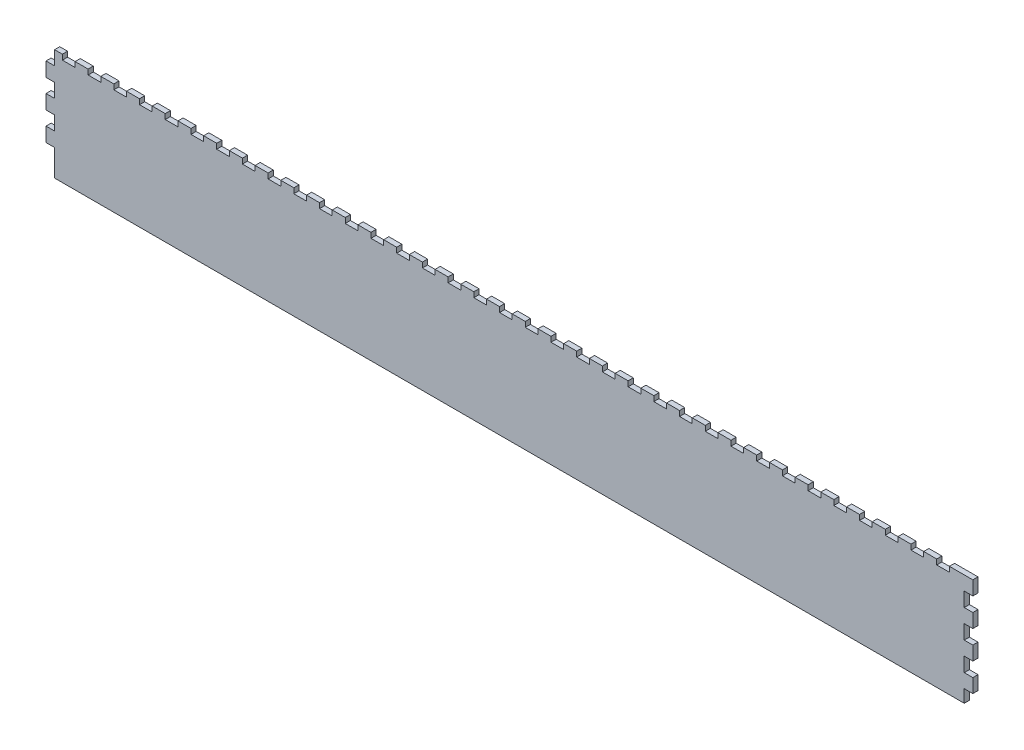
SolidWorks part; units mm, degrees
material "Perspex (TM) GS Acrylic Cast Sheet"
ref_plane "Front Plane" through (0, 0, 0) normal (0, 0, 1) x (1, 0, 0)
ref_plane "Top Plane" through (0, 0, 0) normal (0, 1, 0) x (1, 0, 0)
ref_plane "Right Plane" through (0, 0, 0) normal (1, 0, 0) x (0, 0, -1)
sketch "Sketch1" plane through (0, 0, 0) normal (0, 0, 1) x (1, 0, 0)
  line L0 (4.9997, 15.394) -> (4.9997, 0)
  line L1158 (538.3599, 64.6) -> (524.7414, 64.6)
  line L1159 (524.7414, 61.6) -> (524.7414, 64.6)
  line L1160 (524.7414, 61.6) -> (517.3729, 61.6)
  line L1161 (517.3729, 61.6) -> (517.3729, 64.6)
  line L1162 (517.3729, 64.6) -> (509.8045, 64.6)
  line L1163 (509.8045, 61.6) -> (509.8045, 64.6)
  line L1164 (509.8045, 61.6) -> (502.436, 61.6)
  line L1165 (502.436, 61.6) -> (502.436, 64.6)
  line L1166 (502.436, 64.6) -> (494.8676, 64.6)
  line L1167 (494.8676, 61.6) -> (494.8676, 64.6)
  line L1168 (494.8676, 61.6) -> (487.4991, 61.6)
  line L1169 (487.4991, 61.6) -> (487.4991, 64.6)
  line L1170 (487.4991, 64.6) -> (479.9307, 64.6)
  line L1171 (479.9307, 61.6) -> (479.9307, 64.6)
  line L1172 (479.9307, 61.6) -> (472.5622, 61.6)
  line L1173 (472.5622, 61.6) -> (472.5622, 64.6)
  line L1174 (472.5622, 64.6) -> (464.9938, 64.6)
  line L1175 (464.9938, 61.6) -> (464.9938, 64.6)
  line L1176 (464.9938, 61.6) -> (457.6253, 61.6)
  line L1177 (457.6253, 61.6) -> (457.6253, 64.6)
  line L1178 (457.6253, 64.6) -> (450.0567, 64.6)
  line L1179 (450.0567, 61.6) -> (450.0567, 64.6)
  line L1180 (450.0567, 61.6) -> (442.6886, 61.6)
  line L1181 (442.6886, 61.6) -> (442.6886, 64.6)
  line L1182 (442.6886, 64.6) -> (435.1201, 64.6)
  line L1183 (435.1201, 61.6) -> (435.1201, 64.6)
  line L1184 (435.1201, 61.6) -> (427.7516, 61.6)
  line L1185 (427.7516, 61.6) -> (427.7516, 64.6)
  line L1186 (427.7516, 64.6) -> (420.1831, 64.6)
  line L1187 (420.1831, 61.6) -> (420.1831, 64.6)
  line L1188 (420.1831, 61.6) -> (412.8147, 61.6)
  line L1189 (412.8147, 61.6) -> (412.8147, 64.6)
  line L1190 (412.8147, 64.6) -> (405.2462, 64.6)
  line L1191 (405.2462, 61.6) -> (405.2462, 64.6)
  line L1192 (405.2462, 61.6) -> (397.8777, 61.6)
  line L1193 (397.8777, 61.6) -> (397.8777, 64.6)
  line L1194 (397.8777, 64.6) -> (390.3092, 64.6)
  line L1195 (390.3092, 61.6) -> (390.3092, 64.6)
  line L1196 (390.3092, 61.6) -> (382.9407, 61.6)
  line L1197 (382.9407, 61.6) -> (382.9407, 64.6)
  line L1198 (382.9407, 64.6) -> (375.3722, 64.6)
  line L1199 (375.3722, 61.6) -> (375.3722, 64.6)
  line L1200 (375.3722, 61.6) -> (368.0038, 61.6)
  line L1201 (368.0038, 61.6) -> (368.0038, 64.6)
  line L1202 (368.0038, 64.6) -> (360.4356, 64.6)
  line L1203 (360.4356, 61.6) -> (360.4356, 64.6)
  line L1204 (360.4356, 61.6) -> (353.0672, 61.6)
  line L1205 (353.0672, 61.6) -> (353.0672, 64.6)
  line L1206 (353.0672, 64.6) -> (345.4986, 64.6)
  line L1207 (345.4986, 61.6) -> (345.4986, 64.6)
  line L1208 (345.4986, 61.6) -> (338.1302, 61.6)
  line L1209 (338.1302, 61.6) -> (338.1302, 64.6)
  line L1210 (338.1302, 64.6) -> (330.5617, 64.6)
  line L1211 (330.5617, 61.6) -> (330.5617, 64.6)
  line L1212 (330.5617, 61.6) -> (323.1932, 61.6)
  line L1213 (323.1932, 61.6) -> (323.1932, 64.6)
  line L1214 (323.1932, 64.6) -> (315.6247, 64.6)
  line L1215 (315.6247, 61.6) -> (315.6247, 64.6)
  line L1216 (315.6247, 61.6) -> (308.2563, 61.6)
  line L1217 (308.2563, 61.6) -> (308.2563, 64.6)
  line L1218 (308.2563, 64.6) -> (300.6878, 64.6)
  line L1219 (300.6878, 61.6) -> (300.6878, 64.6)
  line L1220 (300.6878, 61.6) -> (293.3193, 61.6)
  line L1221 (293.3193, 61.6) -> (293.3193, 64.6)
  line L1222 (293.3193, 64.6) -> (285.7508, 64.6)
  line L1223 (285.7508, 61.6) -> (285.7508, 64.6)
  line L1224 (285.7508, 61.6) -> (278.3823, 61.6)
  line L1225 (278.3823, 61.6) -> (278.3823, 64.6)
  line L1226 (278.3823, 64.6) -> (270.8142, 64.6)
  line L1227 (270.8142, 61.6) -> (270.8142, 64.6)
  line L1228 (270.8142, 61.6) -> (263.4457, 61.6)
  line L1229 (263.4457, 61.6) -> (263.4457, 64.6)
  line L1230 (263.4457, 64.6) -> (255.8772, 64.6)
  line L1231 (255.8772, 61.6) -> (255.8772, 64.6)
  line L1232 (255.8772, 61.6) -> (248.5088, 61.6)
  line L1233 (248.5088, 61.6) -> (248.5087, 64.6)
  line L1234 (248.5087, 64.6) -> (240.9403, 64.6)
  line L1235 (240.9403, 61.6) -> (240.9403, 64.6)
  line L1236 (240.9403, 61.6) -> (233.5718, 61.6)
  line L1237 (233.5718, 61.6) -> (233.5718, 64.6)
  line L1238 (233.5718, 64.6) -> (226.0033, 64.6)
  line L1239 (226.0033, 61.6) -> (226.0033, 64.6)
  line L1240 (226.0033, 61.6) -> (218.6348, 61.6)
  line L1241 (218.6348, 61.6) -> (218.6348, 64.6)
  line L1242 (218.6348, 64.6) -> (211.0664, 64.6)
  line L1243 (211.0664, 61.6) -> (211.0664, 64.6)
  line L1244 (211.0664, 61.6) -> (203.6979, 61.6)
  line L1245 (203.6979, 61.6) -> (203.6979, 64.6)
  line L1246 (203.6979, 64.6) -> (196.1297, 64.6)
  line L1247 (196.1297, 61.6) -> (196.1297, 64.6)
  line L1248 (196.1297, 61.6) -> (188.7613, 61.6)
  line L1249 (188.7613, 61.6) -> (188.7613, 64.6)
  line L1250 (188.7613, 64.6) -> (181.1928, 64.6)
  line L1251 (181.1928, 61.6) -> (181.1928, 64.6)
  line L1252 (181.1928, 61.6) -> (173.8243, 61.6)
  line L1253 (173.8243, 61.6) -> (173.8243, 64.6)
  line L1254 (173.8243, 64.6) -> (166.2558, 64.6)
  line L1255 (166.2558, 61.6) -> (166.2558, 64.6)
  line L1256 (166.2558, 61.6) -> (158.8873, 61.6)
  line L1257 (158.8873, 61.6) -> (158.8873, 64.6)
  line L1258 (158.8873, 64.6) -> (151.3188, 64.6)
  line L1259 (151.3188, 61.6) -> (151.3188, 64.6)
  line L1260 (151.3188, 61.6) -> (143.9504, 61.6)
  line L1261 (143.9504, 61.6) -> (143.9504, 64.6)
  line L1262 (143.9504, 64.6) -> (136.3819, 64.6)
  line L1263 (136.3819, 61.6) -> (136.3819, 64.6)
  line L1264 (136.3819, 61.6) -> (129.0134, 61.6)
  line L1265 (129.0134, 61.6) -> (129.0134, 64.6)
  line L1266 (129.0134, 64.6) -> (121.4449, 64.6)
  line L1267 (121.4449, 61.6) -> (121.4449, 64.6)
  line L1268 (121.4449, 61.6) -> (114.0764, 61.6)
  line L1269 (114.0764, 61.6) -> (114.0764, 64.6)
  line L1270 (114.0764, 64.6) -> (106.5083, 64.6)
  line L1271 (106.5083, 61.6) -> (106.5083, 64.6)
  line L1272 (106.5083, 61.6) -> (99.1398, 61.6)
  line L1273 (99.1398, 61.6) -> (99.1398, 64.6)
  line L1274 (99.1398, 64.6) -> (91.5713, 64.6)
  line L1275 (91.5713, 61.6) -> (91.5713, 64.6)
  line L1276 (91.5713, 61.6) -> (84.2029, 61.6)
  line L1277 (84.2029, 61.6) -> (84.2029, 64.6)
  line L1278 (84.2029, 64.6) -> (76.6344, 64.6)
  line L1279 (76.6344, 61.6) -> (76.6344, 64.6)
  line L1280 (76.6344, 61.6) -> (69.2659, 61.6)
  line L1281 (69.2659, 61.6) -> (69.2659, 64.6)
  line L1282 (69.2659, 64.6) -> (61.6974, 64.6)
  line L1283 (61.6974, 61.6) -> (61.6974, 64.6)
  line L1284 (61.6974, 61.6) -> (54.3289, 61.6)
  line L1285 (54.3289, 61.6) -> (54.3289, 64.6)
  line L1286 (54.3289, 64.6) -> (46.7604, 64.6)
  line L1287 (46.7604, 61.6) -> (46.7604, 64.6)
  line L1288 (46.7604, 61.6) -> (39.392, 61.6)
  line L1289 (39.392, 61.6) -> (39.392, 64.6)
  line L1290 (39.392, 64.6) -> (31.8235, 64.6)
  line L1291 (31.8235, 61.6) -> (31.8235, 64.6)
  line L1292 (31.8235, 61.6) -> (24.4554, 61.6)
  line L1293 (24.4554, 61.6) -> (24.4554, 64.6)
  line L1294 (24.4554, 64.6) -> (16.8869, 64.6)
  line L1295 (16.8869, 61.6) -> (16.8869, 64.6)
  line L1296 (16.8869, 61.6) -> (9.5184, 61.6)
  line L1297 (9.5184, 61.6) -> (9.5184, 64.6)
  line L1298 (9.5184, 64.6) -> (4.9997, 64.6)
  line L1299 (538.3599, 64.6) -> (538.3599, 56.4542)
  line L1300 (533.3598, 56.4542) -> (538.3599, 56.4542)
  line L1301 (533.3598, 56.4542) -> (533.3598, 48.1649)
  line L1302 (533.3598, 48.1649) -> (538.3599, 48.1649)
  line L1303 (538.3599, 48.1649) -> (538.3599, 40.0757)
  line L1304 (533.3598, 40.0757) -> (538.3599, 40.0757)
  line L1305 (533.3598, 40.0757) -> (533.3598, 31.7864)
  line L1306 (533.3598, 31.7864) -> (538.3599, 31.7864)
  line L1307 (538.3599, 31.7864) -> (538.3599, 23.7267)
  line L1308 (4.9997, 64.6) -> (4.9997, 56.4542)
  line L1309 (0, 56.4542) -> (4.9997, 56.4542)
  line L1310 (0, 56.4542) -> (0, 48.1649)
  line L1311 (0, 48.1649) -> (4.9997, 48.1649)
  line L1312 (4.9997, 48.1649) -> (4.9997, 40.0757)
  line L1313 (0, 40.0757) -> (4.9997, 40.0757)
  line L1314 (0, 40.0757) -> (0, 31.7864)
  line L1315 (0, 31.7864) -> (4.9997, 31.7864)
  line L1316 (4.9997, 31.7864) -> (4.9997, 23.6833)
  line L1317 (4.9997, 0) -> (533.3598, 0)
  line L1318 (533.3598, 23.7267) -> (538.3599, 23.7267)
  line L1319 (533.3598, 23.7267) -> (533.3598, 15.4209)
  line L1320 (533.3598, 15.4209) -> (538.3599, 15.4209)
  line L1321 (538.3599, 15.4209) -> (538.3599, 7.3612)
  line L1322 (533.3598, 7.3612) -> (538.3599, 7.3612)
  line L1323 (533.3598, 7.3612) -> (533.3598, 0)
  line L1324 (0, 23.6833) -> (4.9997, 23.6833)
  line L1325 (0, 23.6833) -> (0, 15.394)
  line L1326 (0, 15.394) -> (4.9997, 15.394)
extrude "Boss-Extrude1" add sketch "Sketch1" along normal blind 3
sketch "Sketch3" plane through (0, 0, 3) normal (0, 0, 1) x (1, 0, 0)
  line L0 (427.3689, 43.3788) -> (427.3689, 36.9916)
  line L1 (427.3689, 36.9916) -> (432.9032, 36.9916)
  line L2 (432.9032, 36.9916) -> (438.4376, 36.9916)
  line L3 (438.4376, 36.9916) -> (438.4376, 35.1468)
  line L4 (438.4376, 35.1468) -> (438.4376, 33.3021)
  line L5 (438.4376, 33.3021) -> (432.9032, 33.3021)
  line L6 (432.9032, 33.3021) -> (427.3689, 33.3021)
  line L7 (427.3689, 33.3021) -> (427.3689, 21.0804)
  line L8 (427.3689, 21.0804) -> (427.3689, 8.8587)
  line L9 (427.3689, 8.8587) -> (431.0585, 8.8587)
  line L10 (431.0585, 8.8587) -> (434.748, 8.8587)
  line L11 (434.748, 8.8587) -> (434.748, 17.3908)
  line L12 (434.748, 17.3908) -> (434.748, 25.923)
  line L13 (434.748, 25.923) -> (436.5928, 25.923)
  line L14 (436.5928, 25.923) -> (438.4376, 25.923)
  line L15 (438.4376, 25.923) -> (438.4376, 17.3908)
  line L16 (438.4376, 17.3908) -> (438.4376, 8.8587)
  line L17 (438.4376, 8.8587) -> (442.1271, 8.8587)
  line L18 (442.1271, 8.8587) -> (445.8167, 8.8587)
  line L19 (445.8167, 8.8587) -> (445.8133, 26.4994)
  line L20 (444.0744, 29.4972) -> (443.885, 10.7035)
  line L21 (443.885, 10.7035) -> (442.0836, 10.7035)
  line L22 (442.0836, 10.7035) -> (440.2822, 10.7035)
  line L23 (440.2822, 10.7035) -> (440.2822, 19.2356)
  line L24 (440.2822, 19.2356) -> (440.2822, 27.7677)
  line L25 (440.2822, 27.7677) -> (436.5926, 27.7677)
  line L26 (436.5926, 27.7677) -> (432.9031, 27.7677)
  line L27 (432.9031, 27.7677) -> (432.9031, 19.2356)
  line L28 (432.9031, 19.2356) -> (432.9031, 10.7035)
  line L29 (432.9031, 10.7035) -> (431.0583, 10.7035)
  line L30 (431.0583, 10.7035) -> (429.2135, 10.7035)
  line L31 (429.2135, 10.7035) -> (429.2135, 21.0804)
  line L32 (429.2135, 21.0804) -> (429.2135, 31.4573)
  line L33 (429.2135, 31.4573) -> (434.7478, 31.4573)
  line L34 (434.7478, 31.4573) -> (440.2822, 31.4573)
  line L35 (440.2822, 31.4573) -> (440.2822, 35.1468)
  line L36 (440.2822, 35.1468) -> (440.2822, 38.8364)
  line L37 (440.2822, 38.8364) -> (434.8154, 38.8364)
  line L38 (434.8154, 38.8364) -> (429.3486, 38.8364)
  line L39 (429.3486, 38.8364) -> (429.0745, 46.5614)
  line L40 (427.679, 53.4098) -> (427.6792, 53.4098)
  line L41 (317.1431, 29.0623) -> (317.1431, 8.8199)
  line L42 (317.1431, 8.8199) -> (320.7174, 8.9546)
  line L43 (320.7174, 8.9546) -> (324.2916, 9.0893)
  line L44 (324.2916, 9.0893) -> (326.2203, 14.6236)
  line L45 (326.2203, 14.6236) -> (328.149, 20.158)
  line L46 (328.149, 20.158) -> (328.1804, 14.5083)
  line L47 (328.1804, 14.5083) -> (328.2118, 8.8587)
  line L48 (328.2118, 8.8587) -> (331.9014, 8.8587)
  line L49 (331.9014, 8.8587) -> (335.5909, 8.8587)
  line L50 (335.5909, 8.8587) -> (335.5878, 27.6524)
  line L51 (333.8679, 30.4196) -> (333.6625, 10.7035)
  line L52 (333.6625, 10.7035) -> (331.8686, 10.7035)
  line L53 (331.8686, 10.7035) -> (330.0747, 10.7035)
  line L54 (330.0747, 10.7035) -> (329.9504, 20.7161)
  line L55 (329.9504, 20.7161) -> (329.8261, 30.7288)
  line L56 (329.8261, 30.7288) -> (326.41, 20.7161)
  line L57 (326.41, 20.7161) -> (322.9939, 10.7035)
  line L58 (322.9939, 10.7035) -> (321.0268, 10.7035)
  line L59 (321.0268, 10.7035) -> (319.0597, 10.7035)
  line L60 (319.0597, 10.7035) -> (318.8681, 32.2644)
  line L61 (317.4535, 52.9486) -> (317.4534, 52.9486)
  line L62 (299.1565, 42.9176) -> (299.1565, 36.9916)
  line L63 (299.1565, 36.9916) -> (302.846, 36.9916)
  line L64 (302.846, 36.9916) -> (306.5356, 36.9916)
  line L65 (306.5356, 36.9916) -> (306.5325, 40.1047)
  line L66 (304.9009, 43.9062) -> (304.5723, 38.8364)
  line L67 (304.5723, 38.8364) -> (302.8566, 38.8364)
  line L68 (302.8566, 38.8364) -> (301.1409, 38.8364)
  line L69 (301.1409, 38.8364) -> (300.8784, 46.9617)
  line L70 (299.4568, 52.3947) -> (299.4566, 52.3947)
  line L71 (340.6641, 28.8511) -> (340.6641, 8.8587)
  line L72 (340.6641, 8.8587) -> (349.888, 8.8587)
  line L73 (349.888, 8.8587) -> (359.1119, 8.8587)
  line L74 (359.1119, 8.8587) -> (359.1088, 26.73)
  line L75 (357.3698, 29.7278) -> (357.1812, 10.7035)
  line L76 (357.1812, 10.7035) -> (349.8842, 10.7035)
  line L77 (349.8842, 10.7035) -> (342.5872, 10.7035)
  line L78 (342.5872, 10.7035) -> (342.4078, 32.2644)
  line L79 (340.9694, 52.4545) -> (340.9693, 52.4545)
  line L80 (380.7881, 28.8511) -> (380.7881, 8.8587)
  line L81 (380.7881, 8.8587) -> (390.012, 8.8587)
  line L82 (390.012, 8.8587) -> (399.2359, 8.8587)
  line L83 (399.2359, 8.8587) -> (399.2328, 26.73)
  line L84 (397.4938, 29.7278) -> (397.3053, 10.7035)
  line L85 (397.3053, 10.7035) -> (390.0083, 10.7035)
  line L86 (390.0083, 10.7035) -> (382.7113, 10.7035)
  line L87 (382.7113, 10.7035) -> (382.5318, 32.2644)
  line L88 (381.0935, 52.4545) -> (381.0934, 52.4545)
  line L89 (132.8326, 45.6391) -> (132.5214, 38.8364)
  line L90 (132.5214, 38.8364) -> (127.0587, 38.8364)
  line L91 (127.0587, 38.8364) -> (121.5961, 38.8364)
  line L92 (121.5961, 38.8364) -> (121.5961, 35.1468)
  line L93 (121.5961, 35.1468) -> (121.5961, 31.4573)
  line L94 (121.5961, 31.4573) -> (127.1304, 31.4573)
  line L95 (127.1304, 31.4573) -> (132.6648, 31.4573)
  line L96 (132.6648, 31.4573) -> (132.6648, 29.6125)
  line L97 (132.6648, 29.6125) -> (132.6648, 27.7677)
  line L98 (132.6648, 27.7677) -> (127.1304, 27.7677)
  line L99 (127.1304, 27.7677) -> (121.5961, 27.7677)
  line L100 (121.5961, 27.7677) -> (121.5961, 21.0804)
  line L101 (121.5961, 21.0804) -> (121.5961, 14.393)
  line L102 (121.5961, 14.393) -> (125.2857, 14.393)
  line L103 (125.2857, 14.393) -> (128.9752, 14.393)
  line L104 (128.9752, 14.393) -> (128.9752, 17.1602)
  line L105 (128.9752, 17.1602) -> (128.9752, 19.9274)
  line L106 (128.9752, 19.9274) -> (130.82, 19.9274)
  line L107 (130.82, 19.9274) -> (132.6648, 19.9274)
  line L108 (132.6648, 19.9274) -> (132.6648, 15.3154)
  line L109 (132.6648, 15.3154) -> (132.6648, 10.7035)
  line L110 (132.6648, 10.7035) -> (125.3275, 10.7035)
  line L111 (125.3275, 10.7035) -> (117.9903, 10.7035)
  line L112 (117.9903, 10.7035) -> (117.8044, 30.4196)
  line L113 (116.0617, 27.0063) -> (116.0617, 8.8587)
  line L115 (116.0617, 8.8587) -> (125.2857, 8.8587)
  line L116 (125.2857, 8.8587) -> (134.5095, 8.8587)
  line L117 (134.5095, 8.8587) -> (134.5095, 15.3154)
  line L118 (134.5095, 15.3154) -> (134.5095, 21.7722)
  line L119 (134.5095, 21.7722) -> (130.82, 21.7722)
  line L120 (130.82, 21.7722) -> (127.1304, 21.7722)
  line L121 (127.1304, 21.7722) -> (127.1304, 19.005)
  line L122 (127.1304, 19.005) -> (127.1304, 16.2378)
  line L123 (127.1304, 16.2378) -> (125.2857, 16.2378)
  line L124 (125.2857, 16.2378) -> (123.4408, 16.2378)
  line L125 (123.4408, 16.2378) -> (123.4408, 21.0804)
  line L126 (123.4408, 21.0804) -> (123.4408, 25.9229)
  line L127 (123.4408, 25.9229) -> (128.9752, 25.9229)
  line L128 (128.9752, 25.9229) -> (134.5095, 25.9229)
  line L129 (134.5095, 25.9229) -> (134.5095, 29.6125)
  line L130 (134.5095, 29.6125) -> (134.5095, 33.3021)
  line L131 (134.5095, 33.3021) -> (128.9752, 33.3021)
  line L132 (128.9752, 33.3021) -> (123.4408, 33.3021)
  line L133 (123.4408, 33.3021) -> (123.4408, 35.1468)
  line L134 (123.4408, 35.1468) -> (123.4408, 36.9916)
  line L135 (123.4408, 36.9916) -> (128.9752, 36.9916)
  line L136 (128.9752, 36.9916) -> (134.5095, 36.9916)
  line L137 (134.5095, 36.9916) -> (134.4639, 43.5637)
  line L138 (179.4133, 45.6391) -> (179.1021, 38.8364)
  line L139 (179.1021, 38.8364) -> (173.6395, 38.8364)
  line L140 (173.6395, 38.8364) -> (168.1768, 38.8364)
  line L141 (168.1768, 38.8364) -> (168.1768, 35.1468)
  line L142 (168.1768, 35.1468) -> (168.1768, 31.4573)
  line L143 (168.1768, 31.4573) -> (173.7112, 31.4573)
  line L144 (173.7112, 31.4573) -> (179.2455, 31.4573)
  line L145 (179.2455, 31.4573) -> (179.2455, 29.6125)
  line L146 (179.2455, 29.6125) -> (179.2455, 27.7677)
  line L147 (179.2455, 27.7677) -> (173.7112, 27.7677)
  line L148 (173.7112, 27.7677) -> (168.1768, 27.7677)
  line L149 (168.1768, 27.7677) -> (168.1768, 21.0804)
  line L150 (168.1768, 21.0804) -> (168.1768, 14.393)
  line L151 (168.1768, 14.393) -> (171.8664, 14.393)
  line L152 (171.8664, 14.393) -> (175.556, 14.393)
  line L153 (175.556, 14.393) -> (175.556, 17.1602)
  line L154 (175.556, 17.1602) -> (175.556, 19.9274)
  line L155 (175.556, 19.9274) -> (177.4008, 19.9274)
  line L156 (177.4008, 19.9274) -> (179.2455, 19.9274)
  line L157 (179.2455, 19.9274) -> (179.2455, 15.3154)
  line L158 (179.2455, 15.3154) -> (179.2455, 10.7035)
  line L159 (179.2455, 10.7035) -> (171.9083, 10.7035)
  line L160 (171.9083, 10.7035) -> (164.571, 10.7035)
  line L161 (164.571, 10.7035) -> (164.3852, 30.4196)
  line L162 (162.6425, 27.0063) -> (162.6425, 8.8587)
  line L163 (162.6425, 8.8587) -> (171.8664, 8.8587)
  line L164 (171.8664, 8.8587) -> (181.0903, 8.8587)
  line L165 (181.0903, 8.8587) -> (181.0903, 15.3154)
  line L166 (181.0903, 15.3154) -> (181.0903, 21.7722)
  line L167 (181.0903, 21.7722) -> (177.4008, 21.7722)
  line L168 (177.4008, 21.7722) -> (173.7112, 21.7722)
  line L169 (173.7112, 21.7722) -> (173.7112, 19.005)
  line L170 (173.7112, 19.005) -> (173.7112, 16.2378)
  line L171 (173.7112, 16.2378) -> (171.8664, 16.2378)
  line L172 (171.8664, 16.2378) -> (170.0216, 16.2378)
  line L173 (170.0216, 16.2378) -> (170.0216, 21.0804)
  line L174 (170.0216, 21.0804) -> (170.0216, 25.9229)
  line L175 (170.0216, 25.9229) -> (175.556, 25.9229)
  line L176 (175.556, 25.9229) -> (181.0903, 25.9229)
  line L177 (181.0903, 25.9229) -> (181.0903, 29.6125)
  line L178 (181.0903, 29.6125) -> (181.0903, 33.3021)
  line L179 (181.0903, 33.3021) -> (175.556, 33.3021)
  line L180 (175.556, 33.3021) -> (170.0216, 33.3021)
  line L181 (170.0216, 33.3021) -> (170.0216, 35.1468)
  line L182 (170.0216, 35.1468) -> (170.0216, 36.9916)
  line L183 (170.0216, 36.9916) -> (175.556, 36.9916)
  line L184 (175.556, 36.9916) -> (181.0903, 36.9916)
  line L185 (181.0903, 36.9916) -> (181.0447, 43.5637)
  line L186 (264.2733, 45.6391) -> (263.9622, 38.8364)
  line L187 (263.9622, 38.8364) -> (258.4995, 38.8364)
  line L188 (258.4995, 38.8364) -> (253.0369, 38.8364)
  line L189 (253.0369, 38.8364) -> (253.0369, 35.1468)
  line L190 (253.0369, 35.1468) -> (253.0369, 31.4573)
  line L191 (253.0369, 31.4573) -> (258.5712, 31.4573)
  line L192 (258.5712, 31.4573) -> (264.1056, 31.4573)
  line L193 (264.1056, 31.4573) -> (264.1056, 29.6125)
  line L194 (264.1056, 29.6125) -> (264.1056, 27.7677)
  line L195 (264.1056, 27.7677) -> (258.5712, 27.7677)
  line L196 (258.5712, 27.7677) -> (253.0369, 27.7677)
  line L197 (253.0369, 27.7677) -> (253.0369, 21.0804)
  line L198 (253.0369, 21.0804) -> (253.0369, 14.393)
  line L199 (253.0369, 14.393) -> (256.7264, 14.393)
  line L200 (256.7264, 14.393) -> (260.416, 14.393)
  line L201 (260.416, 14.393) -> (260.416, 17.1602)
  line L202 (260.416, 17.1602) -> (260.416, 19.9274)
  line L203 (260.416, 19.9274) -> (262.2608, 19.9274)
  line L204 (262.2608, 19.9274) -> (264.1056, 19.9274)
  line L205 (264.1056, 19.9274) -> (264.1056, 15.3154)
  line L206 (264.1056, 15.3154) -> (264.1056, 10.7035)
  line L207 (264.1056, 10.7035) -> (256.7683, 10.7035)
  line L208 (256.7683, 10.7035) -> (249.4311, 10.7035)
  line L209 (249.4311, 10.7035) -> (249.2452, 30.4196)
  line L210 (247.5025, 27.0063) -> (247.5025, 8.8587)
  line L211 (247.5025, 8.8587) -> (256.7264, 8.8587)
  line L212 (256.7264, 8.8587) -> (265.9504, 8.8587)
  line L213 (265.9504, 8.8587) -> (265.9504, 15.3154)
  line L214 (265.9504, 15.3154) -> (265.9504, 21.7722)
  line L215 (265.9504, 21.7722) -> (262.2608, 21.7722)
  line L216 (262.2608, 21.7722) -> (258.5712, 21.7722)
  line L217 (258.5712, 21.7722) -> (258.5712, 19.005)
  line L218 (258.5712, 19.005) -> (258.5712, 16.2378)
  line L219 (258.5712, 16.2378) -> (256.7264, 16.2378)
  line L220 (256.7264, 16.2378) -> (254.8817, 16.2378)
  line L221 (254.8817, 16.2378) -> (254.8817, 21.0804)
  line L222 (254.8817, 21.0804) -> (254.8817, 25.9229)
  line L223 (254.8817, 25.9229) -> (260.416, 25.9229)
  line L224 (260.416, 25.9229) -> (265.9504, 25.9229)
  line L225 (265.9504, 25.9229) -> (265.9504, 29.6125)
  line L226 (265.9504, 29.6125) -> (265.9504, 33.3021)
  line L227 (265.9504, 33.3021) -> (260.416, 33.3021)
  line L228 (260.416, 33.3021) -> (254.8817, 33.3021)
  line L229 (254.8817, 33.3021) -> (254.8817, 35.1468)
  line L230 (254.8817, 35.1468) -> (254.8817, 36.9916)
  line L231 (254.8817, 36.9916) -> (260.416, 36.9916)
  line L232 (260.416, 36.9916) -> (265.9504, 36.9916)
  line L233 (265.9504, 36.9916) -> (265.9048, 43.5637)
  line L234 (139.1215, 28.1593) -> (139.1215, 8.8587)
  line L235 (139.1215, 8.8587) -> (148.3454, 8.8587)
  line L236 (148.3454, 8.8587) -> (157.5694, 8.8587)
  line L237 (157.5694, 8.8587) -> (157.5694, 18.0826)
  line L238 (155.0474, 28.419) -> (153.2173, 29.5267)
  line L239 (153.2173, 29.5267) -> (155.3933, 30.5839)
  line L240 (155.3933, 30.5839) -> (157.5694, 31.6411)
  line L241 (157.5694, 31.6411) -> (157.5237, 38.813)
  line L242 (155.7798, 40.2285) -> (155.494, 32.6103)
  line L243 (155.494, 32.6103) -> (152.871, 31.2171)
  line L244 (152.6724, 27.6912) -> (155.7246, 26.1862)
  line L245 (155.7246, 26.1862) -> (155.7246, 18.4448)
  line L246 (155.7246, 18.4448) -> (155.7246, 10.7035)
  line L247 (155.7246, 10.7035) -> (148.3856, 10.7035)
  line L248 (148.3856, 10.7035) -> (141.0465, 10.7035)
  line L249 (141.0465, 10.7035) -> (140.8647, 31.5726)
  line L250 (185.7023, 28.1593) -> (185.7023, 8.8587)
  line L251 (185.7023, 8.8587) -> (189.3919, 8.8587)
  line L252 (189.3919, 8.8587) -> (193.0814, 8.8587)
  line L253 (193.0814, 8.8587) -> (193.0814, 22.9252)
  line L254 (193.0814, 22.9252) -> (193.0814, 36.9916)
  line L255 (193.0814, 36.9916) -> (195.8486, 36.9916)
  line L256 (195.8486, 36.9916) -> (198.6158, 36.9916)
  line L257 (198.6158, 36.9916) -> (198.6127, 40.3353)
  line L258 (196.9651, 44.0249) -> (196.6398, 38.8364)
  line L259 (196.6398, 38.8364) -> (193.9383, 38.8364)
  line L260 (193.9383, 38.8364) -> (191.2368, 38.8364)
  line L261 (191.2368, 38.8364) -> (191.2368, 24.7699)
  line L262 (191.2368, 24.7699) -> (191.2368, 10.7035)
  line L263 (191.2368, 10.7035) -> (189.4321, 10.7035)
  line L264 (189.4321, 10.7035) -> (187.6274, 10.7035)
  line L265 (187.6274, 10.7035) -> (187.4457, 31.5726)
  line L266 (186.0076, 51.0709) -> (186.0075, 51.0709)
  line L267 (287.3183, 42.6413) -> (287.0333, 33.3021)
  line L268 (287.0333, 33.3021) -> (285.2545, 33.3021)
  line L269 (285.2545, 33.3021) -> (283.4758, 33.3021)
  line L270 (283.4758, 33.3021) -> (283.4758, 36.0692)
  line L271 (283.4758, 36.0692) -> (283.4758, 38.8364)
  line L272 (283.4758, 38.8364) -> (279.7862, 38.8364)
  line L273 (279.7862, 38.8364) -> (276.0967, 38.8364)
  line L274 (276.0967, 38.8364) -> (276.0967, 26.6147)
  line L275 (276.0967, 26.6147) -> (276.0967, 14.393)
  line L276 (276.0967, 14.393) -> (279.7862, 14.393)
  line L277 (279.7862, 14.393) -> (283.4758, 14.393)
  line L278 (283.4758, 14.393) -> (283.4758, 17.1602)
  line L279 (283.4758, 17.1602) -> (283.4758, 19.9274)
  line L280 (283.4758, 19.9274) -> (285.3206, 19.9274)
  line L281 (285.3206, 19.9274) -> (287.1654, 19.9274)
  line L282 (287.1654, 19.9274) -> (287.1654, 15.3154)
  line L283 (287.1654, 15.3154) -> (287.1654, 10.7035)
  line L284 (287.1654, 10.7035) -> (279.8292, 10.7035)
  line L285 (279.8292, 10.7035) -> (272.4931, 10.7035)
  line L286 (272.4931, 10.7035) -> (272.3046, 29.7278)
  line L287 (270.5623, 26.3146) -> (270.5623, 8.8587)
  line L288 (270.5623, 8.8587) -> (279.7862, 8.8587)
  line L289 (279.7862, 8.8587) -> (289.0102, 8.8587)
  line L290 (289.0102, 8.8587) -> (289.0102, 15.3154)
  line L291 (289.0102, 15.3154) -> (289.0102, 21.7722)
  line L292 (289.0102, 21.7722) -> (285.3206, 21.7722)
  line L293 (285.3206, 21.7722) -> (281.631, 21.7722)
  line L294 (281.631, 21.7722) -> (281.631, 19.005)
  line L295 (281.631, 19.005) -> (281.631, 16.2378)
  line L296 (281.631, 16.2378) -> (279.7862, 16.2378)
  line L297 (279.7862, 16.2378) -> (277.9415, 16.2378)
  line L298 (277.9415, 16.2378) -> (277.9415, 26.6147)
  line L299 (277.9415, 26.6147) -> (277.9415, 36.9916)
  line L300 (277.9415, 36.9916) -> (279.7862, 36.9916)
  line L301 (279.7862, 36.9916) -> (281.631, 36.9916)
  line L302 (281.631, 36.9916) -> (281.631, 34.2245)
  line L303 (281.631, 34.2245) -> (281.631, 31.4573)
  line L304 (281.631, 31.4573) -> (285.3206, 31.4573)
  line L305 (285.3206, 31.4573) -> (289.0102, 31.4573)
  line L306 (289.0102, 31.4573) -> (288.9645, 40.5659)
  line L307 (364.1851, 28.1593) -> (364.1851, 8.8587)
  line L308 (364.1851, 8.8587) -> (367.8746, 8.8587)
  line L309 (367.8746, 8.8587) -> (371.5642, 8.8587)
  line L310 (371.5642, 8.8587) -> (371.5642, 22.9252)
  line L311 (371.5642, 22.9252) -> (371.5642, 36.9916)
  line L312 (371.5642, 36.9916) -> (374.3314, 36.9916)
  line L313 (374.3314, 36.9916) -> (377.0985, 36.9916)
  line L314 (377.0985, 36.9916) -> (377.0954, 40.3353)
  line L315 (375.4479, 44.0249) -> (375.1226, 38.8364)
  line L316 (375.1226, 38.8364) -> (372.4211, 38.8364)
  line L317 (372.4211, 38.8364) -> (369.7196, 38.8364)
  line L318 (369.7196, 38.8364) -> (369.7196, 24.7699)
  line L319 (369.7196, 24.7699) -> (369.7196, 10.7035)
  line L320 (369.7196, 10.7035) -> (367.9149, 10.7035)
  line L321 (367.9149, 10.7035) -> (366.1102, 10.7035)
  line L322 (366.1102, 10.7035) -> (365.9284, 31.5726)
  line L323 (364.4904, 51.0709) -> (364.4903, 51.0709)
  line L324 (421.0584, 39.6435) -> (420.7948, 27.7677)
  line L325 (420.7948, 27.7677) -> (419.0087, 27.7677)
  line L326 (419.0087, 27.7677) -> (417.2226, 27.7677)
  line L327 (417.2226, 27.7677) -> (417.2226, 33.3021)
  line L328 (417.2226, 33.3021) -> (417.2226, 38.8364)
  line L329 (417.2226, 38.8364) -> (413.533, 38.8364)
  line L330 (413.533, 38.8364) -> (409.8435, 38.8364)
  line L331 (409.8435, 38.8364) -> (409.8435, 26.6147)
  line L332 (409.8435, 26.6147) -> (409.8435, 14.393)
  line L333 (409.8435, 14.393) -> (413.533, 14.393)
  line L334 (413.533, 14.393) -> (417.2226, 14.393)
  line L335 (417.2226, 14.393) -> (417.2226, 17.1602)
  line L336 (417.2226, 17.1602) -> (417.2226, 19.9274)
  line L337 (417.2226, 19.9274) -> (419.0674, 19.9274)
  line L338 (419.0674, 19.9274) -> (420.9122, 19.9274)
  line L339 (420.9122, 19.9274) -> (420.9122, 15.3154)
  line L340 (420.9122, 15.3154) -> (420.9122, 10.7035)
  line L341 (420.9122, 10.7035) -> (413.5729, 10.7035)
  line L342 (413.5729, 10.7035) -> (406.2336, 10.7035)
  line L343 (406.2336, 10.7035) -> (406.0524, 29.4972)
  line L344 (404.3091, 26.084) -> (404.3091, 8.8587)
  line L345 (404.3091, 8.8587) -> (413.533, 8.8587)
  line L346 (413.533, 8.8587) -> (422.7569, 8.8587)
  line L347 (422.7569, 8.8587) -> (422.7569, 15.3154)
  line L348 (422.7569, 15.3154) -> (422.7569, 21.7722)
  line L349 (422.7569, 21.7722) -> (419.0674, 21.7722)
  line L350 (419.0674, 21.7722) -> (415.3778, 21.7722)
  line L351 (415.3778, 21.7722) -> (415.3778, 19.005)
  line L352 (415.3778, 19.005) -> (415.3778, 16.2378)
  line L353 (415.3778, 16.2378) -> (413.533, 16.2378)
  line L354 (413.533, 16.2378) -> (411.6882, 16.2378)
  line L355 (411.6882, 16.2378) -> (411.6882, 26.6147)
  line L356 (411.6882, 26.6147) -> (411.6882, 36.9916)
  line L357 (411.6882, 36.9916) -> (413.533, 36.9916)
  line L358 (413.533, 36.9916) -> (415.3778, 36.9916)
  line L359 (415.3778, 36.9916) -> (415.3778, 31.4573)
  line L360 (415.3778, 31.4573) -> (415.3778, 25.9229)
  line L361 (415.3778, 25.9229) -> (419.0674, 25.9229)
  line L362 (419.0674, 25.9229) -> (422.7569, 25.9229)
  line L363 (422.7569, 25.9229) -> (422.7113, 37.5681)
  line L364 (310.3498, 30.4196) -> (310.1348, 10.7035)
  line L365 (310.1348, 10.7035) -> (308.3352, 10.7035)
  line L366 (308.3352, 10.7035) -> (306.5356, 10.7035)
  line L367 (306.5356, 10.7035) -> (306.5356, 22.0028)
  line L368 (306.5356, 22.0028) -> (306.5356, 33.3021)
  line L369 (306.5356, 33.3021) -> (302.846, 33.3021)
  line L370 (302.846, 33.3021) -> (299.1565, 33.3021)
  line L371 (299.1565, 33.3021) -> (299.1565, 22.0028)
  line L372 (299.1565, 22.0028) -> (299.1565, 10.7035)
  line L373 (299.1565, 10.7035) -> (297.3511, 10.7035)
  line L374 (297.3511, 10.7035) -> (295.5459, 10.7035)
  line L375 (295.5459, 10.7035) -> (295.346, 29.7278)
  line L376 (293.6249, 26.2688) -> (293.6221, 8.8587)
  line L377 (293.6221, 8.8587) -> (297.3116, 8.8587)
  line L378 (297.3116, 8.8587) -> (301.0012, 8.8587)
  line L379 (301.0012, 8.8587) -> (301.0012, 20.158)
  line L380 (301.0012, 20.158) -> (301.0012, 31.4573)
  line L381 (301.0012, 31.4573) -> (302.846, 31.4573)
  line L382 (302.846, 31.4573) -> (304.6908, 31.4573)
  line L383 (304.6908, 31.4573) -> (304.6908, 20.158)
  line L384 (304.6908, 20.158) -> (304.6908, 8.8587)
  line L385 (304.6908, 8.8587) -> (308.3803, 8.8587)
  line L386 (308.3803, 8.8587) -> (312.0699, 8.8587)
  line L387 (312.0699, 8.8587) -> (312.0243, 28.1136)
  line L388 (326.6972, 38.8364) -> (324.7528, 33.0715)
  line L389 (324.7528, 33.0715) -> (324.4665, 39.9894)
  line L390 (328.9784, 48.2909) -> (328.9785, 48.2909)
  line L391 (92.5407, 26.5451) -> (92.5407, 8.8587)
  line L392 (92.5407, 8.8587) -> (101.7647, 8.8587)
  line L393 (101.7647, 8.8587) -> (110.9886, 8.8587)
  line L394 (110.9886, 8.8587) -> (110.9886, 20.8409)
  line L395 (110.9886, 20.8409) -> (110.9886, 32.8232)
  line L396 (110.9886, 32.8232) -> (108.7994, 33.9357)
  line L397 (108.7994, 33.9357) -> (106.6103, 35.0483)
  line L398 (106.6103, 35.0483) -> (108.7994, 36.1119)
  line L399 (108.7994, 36.1119) -> (110.9886, 37.1754)
  line L400 (110.9886, 37.1754) -> (110.9429, 41.8108)
  line L401 (109.2518, 43.2178) -> (108.9132, 38.1446)
  line L402 (108.9132, 38.1446) -> (106.2902, 36.7515)
  line L403 (106.0917, 33.2256) -> (109.1438, 31.7205)
  line L404 (109.1438, 31.7205) -> (109.1438, 21.212)
  line L405 (109.1438, 21.212) -> (109.1438, 10.7035)
  line L406 (109.1438, 10.7035) -> (101.8073, 10.7035)
  line L407 (101.8073, 10.7035) -> (94.4708, 10.7035)
  line L408 (94.4708, 10.7035) -> (94.2831, 29.9584)
  line L409 (98.0751, 40.3496) -> (98.0751, 36.9289)
  line L410 (98.0751, 36.9289) -> (101.7642, 38.9203)
  line L411 (103.8574, 46.0593) -> (103.5335, 41.7382)
  line L412 (103.5335, 41.7382) -> (101.9416, 40.9791)
  line L413 (230.4383, 30.0041) -> (230.4383, 16.2378)
  line L414 (230.4383, 16.2378) -> (227.6711, 16.2378)
  line L415 (227.6711, 16.2378) -> (224.9039, 16.2378)
  line L416 (224.9039, 16.2378) -> (224.9039, 12.5483)
  line L417 (224.9039, 12.5483) -> (224.9039, 8.8587)
  line L418 (224.9039, 8.8587) -> (234.1279, 8.8587)
  line L419 (234.1279, 8.8587) -> (243.3518, 8.8587)
  line L420 (243.3518, 8.8587) -> (243.3518, 12.5483)
  line L421 (243.3518, 12.5483) -> (243.3518, 16.2378)
  line L422 (243.3518, 16.2378) -> (240.5846, 16.2378)
  line L423 (240.5846, 16.2378) -> (237.8174, 16.2378)
  line L424 (237.8174, 16.2378) -> (237.8143, 30.4196)
  line L425 (236.0427, 32.1262) -> (235.8819, 14.393)
  line L426 (235.8819, 14.393) -> (238.6945, 14.393)
  line L427 (238.6945, 14.393) -> (241.5071, 14.393)
  line L428 (241.5071, 14.393) -> (241.5071, 12.5483)
  line L429 (241.5071, 12.5483) -> (241.5071, 10.7035)
  line L430 (241.5071, 10.7035) -> (234.128, 10.7035)
  line L431 (234.128, 10.7035) -> (226.7489, 10.7035)
  line L432 (226.7489, 10.7035) -> (226.7489, 12.5483)
  line L433 (226.7489, 12.5483) -> (226.7489, 14.393)
  line L434 (226.7489, 14.393) -> (229.5578, 14.393)
  line L435 (229.5578, 14.393) -> (232.3668, 14.393)
  line L436 (232.3668, 14.393) -> (232.2097, 32.1264)
  line L437 (230.7386, 47.3216) -> (230.7385, 47.3216)
  line L438 (144.6559, 35.1417) -> (144.6559, 31.447)
  line L439 (144.6559, 31.447) -> (148.3454, 33.3021)
  line L440 (152.035, 36.9968) -> (152.035, 38.8364)
  line L441 (152.035, 38.8364) -> (148.3454, 38.8364)
  line L442 (148.3454, 38.8364) -> (144.6559, 38.8364)
  line L443 (144.6559, 38.8364) -> (144.6559, 35.1417)
  line L444 (346.1984, 26.6147) -> (346.1984, 14.393)
  line L445 (346.1984, 14.393) -> (349.888, 14.393)
  line L446 (349.888, 14.393) -> (353.5776, 14.393)
  line L447 (353.5776, 14.393) -> (353.5776, 26.6147)
  line L448 (353.5776, 26.6147) -> (353.5776, 38.8364)
  line L449 (353.5776, 38.8364) -> (349.888, 38.8364)
  line L450 (349.888, 38.8364) -> (346.1984, 38.8364)
  line L451 (346.1984, 38.8364) -> (346.1984, 26.6147)
  line L452 (351.7328, 26.6147) -> (351.7328, 16.2378)
  line L453 (351.7328, 16.2378) -> (349.888, 16.2378)
  line L454 (349.888, 16.2378) -> (348.0432, 16.2378)
  line L455 (348.0432, 16.2378) -> (348.0432, 26.6147)
  line L456 (348.0432, 26.6147) -> (348.0432, 36.9916)
  line L457 (348.0432, 36.9916) -> (349.888, 36.9916)
  line L458 (349.888, 36.9916) -> (351.7328, 36.9916)
  line L459 (351.7328, 36.9916) -> (351.7328, 26.6147)
  line L460 (386.3225, 26.6147) -> (386.3225, 14.393)
  line L461 (386.3225, 14.393) -> (390.012, 14.393)
  line L462 (390.012, 14.393) -> (393.7016, 14.393)
  line L463 (393.7016, 14.393) -> (393.7016, 26.6147)
  line L464 (393.7016, 26.6147) -> (393.7016, 38.8364)
  line L465 (393.7016, 38.8364) -> (390.012, 38.8364)
  line L466 (390.012, 38.8364) -> (386.3225, 38.8364)
  line L467 (386.3225, 38.8364) -> (386.3225, 26.6147)
  line L468 (391.8568, 26.6147) -> (391.8568, 16.2378)
  line L469 (391.8568, 16.2378) -> (390.012, 16.2378)
  line L470 (390.012, 16.2378) -> (388.1672, 16.2378)
  line L471 (388.1672, 16.2378) -> (388.1672, 26.6147)
  line L472 (388.1672, 26.6147) -> (388.1672, 36.9916)
  line L473 (388.1672, 36.9916) -> (390.012, 36.9916)
  line L474 (390.012, 36.9916) -> (391.8568, 36.9916)
  line L475 (391.8568, 36.9916) -> (391.8568, 26.6147)
  line L476 (98.0751, 23.617) -> (98.0751, 14.393)
  line L477 (98.0751, 14.393) -> (101.7647, 14.393)
  line L478 (101.7647, 14.393) -> (105.4542, 14.393)
  line L479 (105.4542, 14.393) -> (105.4542, 21.7305)
  line L480 (105.4542, 21.7305) -> (105.4542, 29.0679)
  line L481 (105.4542, 29.0679) -> (102.017, 30.9544)
  line L482 (103.6094, 22.224) -> (103.6094, 16.2378)
  line L483 (103.6094, 16.2378) -> (101.7647, 16.2378)
  line L484 (101.7647, 16.2378) -> (99.9199, 16.2378)
  line L485 (99.9199, 16.2378) -> (99.9199, 23.1651)
  line L486 (99.9199, 23.1651) -> (99.9199, 30.0924)
  line L487 (99.9199, 30.0924) -> (101.7647, 29.1513)
  line L488 (101.7647, 29.1513) -> (103.6094, 28.2102)
  line L489 (103.6094, 28.2102) -> (103.6094, 22.224)
  line L490 (144.6559, 20.8549) -> (144.6559, 14.393)
  line L491 (144.6559, 14.393) -> (148.3454, 14.393)
  line L492 (148.3454, 14.393) -> (152.035, 14.393)
  line L493 (152.035, 14.393) -> (152.035, 18.9998)
  line L494 (152.035, 18.9998) -> (152.035, 23.6067)
  line L495 (152.035, 23.6067) -> (148.3454, 25.4617)
  line L496 (148.3454, 25.4617) -> (144.6559, 27.3168)
  line L497 (144.6559, 27.3168) -> (144.6559, 20.8549)
  line L498 (150.1902, 19.4568) -> (150.1902, 16.2378)
  line L499 (150.1902, 16.2378) -> (148.3454, 16.2378)
  line L500 (148.3454, 16.2378) -> (146.5007, 16.2378)
  line L501 (146.5007, 16.2378) -> (146.5007, 20.398)
  line L502 (146.5007, 20.398) -> (146.5007, 24.5581)
  line L503 (146.5007, 24.5581) -> (148.3454, 23.617)
  line L504 (148.3454, 23.617) -> (150.1902, 22.6758)
  line L505 (150.1902, 22.6758) -> (150.1902, 19.4568)
  spline S0 degree 3 poles (427.6792, 53.4098) (427.5085, 51.4057) (427.3689, 46.8917) (427.3689, 43.3788) knots 0 0 0 0 1 1 1 1
  spline S1 degree 3 poles (445.8133, 26.4994) (445.8097, 45.5926) (445.5401, 51.3252) (444.7352, 49.4116) knots 0 0 0 0 1 1 1 1
  spline S2 degree 3 poles (444.7352, 49.4116) (444.4517, 48.7374) (444.1884, 40.8031) (444.0744, 29.4972) knots 0 0 0 0 1 1 1 1
  spline S3 degree 3 poles (317.4534, 52.9486) (317.2827, 50.9445) (317.1431, 40.1957) (317.1431, 29.0623) knots 0 0 0 0 1 1 1 1
  spline S4 degree 3 poles (335.5878, 27.6524) (335.585, 37.989) (335.4464, 47.8989) (335.2775, 49.6745) knots 0 0 0 0 1 1 1 1
  spline S5 degree 3 poles (335.2775, 49.6745) (334.5923, 56.8796) (334.069, 49.7317) (333.8679, 30.4196) knots 0 0 0 0 1 1 1 1
  spline S6 degree 3 poles (318.8681, 32.2644) (318.7578, 44.6761) (318.4828, 54.4124) (318.2202, 55.2089) knots 0 0 0 0 1 1 1 1
  spline S7 degree 3 poles (299.4566, 52.3947) (299.2915, 50.4416) (299.1565, 46.1769) (299.1565, 42.9176) knots 0 0 0 0 1 1 1 1
  spline S8 degree 3 poles (306.5325, 40.1047) (306.528, 44.4858) (306.0105, 49.4588) (305.5866, 49.1968) knots 0 0 0 0 1 1 1 1
  spline S9 degree 3 poles (305.5866, 49.1968) (305.3902, 49.0754) (305.0816, 46.6946) (304.9009, 43.9062) knots 0 0 0 0 1 1 1 1
  spline S10 degree 3 poles (340.9693, 52.4545) (340.8014, 50.4685) (340.6641, 39.8469) (340.6641, 28.8511) knots 0 0 0 0 1 1 1 1
  spline S11 degree 3 poles (359.1088, 26.73) (359.1051, 46.0456) (358.8375, 51.7903) (358.0302, 49.8728) knots 0 0 0 0 1 1 1 1
  spline S12 degree 3 poles (358.0302, 49.8728) (357.7454, 49.1965) (357.4836, 41.209) (357.3698, 29.7278) knots 0 0 0 0 1 1 1 1
  spline S13 degree 3 poles (342.4078, 32.2644) (342.2962, 45.6623) (342.0477, 54.2493) (341.7514, 54.9454) knots 0 0 0 0 1 1 1 1
  spline S14 degree 3 poles (341.7514, 54.9454) (341.3483, 55.8926) (341.2276, 55.5082) (340.9694, 52.4545) knots 0 0 0 0 1 1 1 1
  spline S15 degree 3 poles (381.0934, 52.4545) (380.9255, 50.4685) (380.7881, 39.8469) (380.7881, 28.8511) knots 0 0 0 0 1 1 1 1
  spline S16 degree 3 poles (399.2328, 26.73) (399.2292, 46.0456) (398.9616, 51.7903) (398.1542, 49.8728) knots 0 0 0 0 1 1 1 1
  spline S17 degree 3 poles (398.1542, 49.8728) (397.8694, 49.1965) (397.6076, 41.209) (397.4938, 29.7278) knots 0 0 0 0 1 1 1 1
  spline S18 degree 3 poles (382.5318, 32.2644) (382.4202, 45.6623) (382.1718, 54.2493) (381.8755, 54.9454) knots 0 0 0 0 1 1 1 1
  spline S19 degree 3 poles (381.8755, 54.9454) (381.4723, 55.8926) (381.3516, 55.5082) (381.0935, 52.4545) knots 0 0 0 0 1 1 1 1
  spline S20 degree 3 poles (133.4689, 53.8253) (133.2901, 53.0643) (133.0037, 49.3805) (132.8326, 45.6391) knots 0 0 0 0 1 1 1 1
  spline S21 degree 3 poles (117.8044, 30.4196) (117.6912, 42.4205) (117.4333, 50.574) (117.1453, 51.2558) knots 0 0 0 0 1 1 1 1
  spline S22 degree 3 poles (117.1453, 51.2558) (116.3465, 53.1468) (116.0617, 46.7731) (116.0617, 27.0063) knots 0 0 0 0 1 1 1 1
  spline S23 degree 3 poles (134.4639, 43.5637) (134.4388, 47.1783) (134.2779, 51.2772) (134.1062, 52.6723) knots 0 0 0 0 1 1 1 1
  spline S24 degree 3 poles (134.1062, 52.6723) (133.8268, 54.9434) (133.7601, 55.0641) (133.4689, 53.8253) knots 0 0 0 0 1 1 1 1
  spline S25 degree 3 poles (180.0497, 53.8253) (179.8708, 53.0643) (179.5845, 49.3805) (179.4133, 45.6391) knots 0 0 0 0 1 1 1 1
  spline S26 degree 3 poles (164.3852, 30.4196) (164.272, 42.4205) (164.0141, 50.574) (163.7261, 51.2558) knots 0 0 0 0 1 1 1 1
  spline S27 degree 3 poles (163.7261, 51.2558) (162.9273, 53.1468) (162.6425, 46.7731) (162.6425, 27.0063) knots 0 0 0 0 1 1 1 1
  spline S28 degree 3 poles (181.0447, 43.5637) (181.0196, 47.1783) (180.8587, 51.2772) (180.687, 52.6723) knots 0 0 0 0 1 1 1 1
  spline S29 degree 3 poles (180.687, 52.6723) (180.4076, 54.9434) (180.3409, 55.0641) (180.0497, 53.8253) knots 0 0 0 0 1 1 1 1
  spline S30 degree 3 poles (264.9097, 53.8253) (264.7309, 53.0643) (264.4445, 49.3805) (264.2733, 45.6391) knots 0 0 0 0 1 1 1 1
  spline S31 degree 3 poles (249.2452, 30.4196) (249.132, 42.4205) (248.8741, 50.574) (248.5861, 51.2558) knots 0 0 0 0 1 1 1 1
  spline S32 degree 3 poles (248.5861, 51.2558) (247.7874, 53.1468) (247.5025, 46.7731) (247.5025, 27.0063) knots 0 0 0 0 1 1 1 1
  spline S33 degree 3 poles (265.9048, 43.5637) (265.8796, 47.1783) (265.7187, 51.2772) (265.547, 52.6723) knots 0 0 0 0 1 1 1 1
  spline S34 degree 3 poles (265.547, 52.6723) (265.2676, 54.9434) (265.2009, 55.0641) (264.9097, 53.8253) knots 0 0 0 0 1 1 1 1
  spline S35 degree 3 poles (139.4268, 51.0709) (139.2589, 49.0849) (139.1215, 38.7747) (139.1215, 28.1593) knots 0 0 0 0 1 1 1 1
  spline S36 degree 3 poles (157.5694, 18.0826) (157.5694, 23.1558) (157.4137, 27.3076) (157.2235, 27.3089) knots 0 0 0 0 1 1 1 1
  spline S37 degree 3 poles (157.2235, 27.3089) (157.0332, 27.3089) (156.054, 27.8097) (155.0474, 28.419) knots 0 0 0 0 1 1 1 1
  spline S38 degree 3 poles (157.5237, 38.813) (157.4986, 42.7576) (157.3347, 47.1264) (157.1594, 48.5215) knots 0 0 0 0 1 1 1 1
  spline S39 degree 3 poles (157.1594, 48.5215) (156.8418, 51.0495) (156.8394, 51.0527) (156.4531, 49.4524) knots 0 0 0 0 1 1 1 1
  spline S40 degree 3 poles (156.4531, 49.4524) (156.2399, 48.5692) (155.9369, 44.4184) (155.7798, 40.2285) knots 0 0 0 0 1 1 1 1
  spline S41 degree 3 poles (152.871, 31.2171) (151.4283, 30.4509) (150.1068, 29.6828) (149.9341, 29.5102) knots 0 0 0 0 1 1 1 1
  spline S42 degree 3 poles (149.9341, 29.5102) (149.7615, 29.3375) (150.9937, 28.519) (152.6724, 27.6912) knots 0 0 0 0 1 1 1 1
  spline S43 degree 3 poles (140.8647, 31.5726) (140.7526, 44.4472) (140.5008, 52.8708) (140.2075, 53.5618) knots 0 0 0 0 1 1 1 1
  spline S44 degree 3 poles (140.2075, 53.5618) (139.8058, 54.508) (139.6846, 54.1213) (139.4268, 51.0709) knots 0 0 0 0 1 1 1 1
  spline S45 degree 3 poles (186.0075, 51.0709) (185.8396, 49.0849) (185.7023, 38.7747) (185.7023, 28.1593) knots 0 0 0 0 1 1 1 1
  spline S46 degree 3 poles (198.6127, 40.3353) (198.6082, 45.0041) (198.0876, 50.0236) (197.6537, 49.5826) knots 0 0 0 0 1 1 1 1
  spline S47 degree 3 poles (197.6537, 49.5826) (197.4539, 49.3795) (197.1441, 46.8785) (196.9651, 44.0249) knots 0 0 0 0 1 1 1 1
  spline S48 degree 3 poles (187.4457, 31.5726) (187.3335, 44.4472) (187.0817, 52.8708) (186.7884, 53.5618) knots 0 0 0 0 1 1 1 1
  spline S49 degree 3 poles (186.7884, 53.5618) (186.3867, 54.508) (186.2655, 54.1213) (186.0076, 51.0709) knots 0 0 0 0 1 1 1 1
  spline S50 degree 3 poles (287.9491, 53.3641) (287.7589, 52.6031) (287.4751, 47.7778) (287.3183, 42.6413) knots 0 0 0 0 1 1 1 1
  spline S51 degree 3 poles (272.3046, 29.7278) (272.1908, 41.2035) (271.9289, 49.1966) (271.6444, 49.8722) knots 0 0 0 0 1 1 1 1
  spline S52 degree 3 poles (271.6444, 49.8722) (270.8533, 51.751) (270.5623, 45.4157) (270.5623, 26.3146) knots 0 0 0 0 1 1 1 1
  spline S53 degree 3 poles (288.9645, 40.5659) (288.9394, 45.5756) (288.7785, 50.816) (288.6068, 52.2111) knots 0 0 0 0 1 1 1 1
  spline S54 degree 3 poles (288.6068, 52.2111) (288.3235, 54.5141) (288.2629, 54.6203) (287.9491, 53.3641) knots 0 0 0 0 1 1 1 1
  spline S55 degree 3 poles (364.4903, 51.0709) (364.3224, 49.0849) (364.1851, 38.7747) (364.1851, 28.1593) knots 0 0 0 0 1 1 1 1
  spline S56 degree 3 poles (377.0954, 40.3353) (377.0909, 45.0041) (376.5704, 50.0236) (376.1365, 49.5826) knots 0 0 0 0 1 1 1 1
  spline S57 degree 3 poles (376.1365, 49.5826) (375.9367, 49.3795) (375.6268, 46.8785) (375.4479, 44.0249) knots 0 0 0 0 1 1 1 1
  spline S58 degree 3 poles (365.9284, 31.5726) (365.8163, 44.4472) (365.5645, 52.8708) (365.2711, 53.5618) knots 0 0 0 0 1 1 1 1
  spline S59 degree 3 poles (365.2711, 53.5618) (364.8695, 54.508) (364.7483, 54.1213) (364.4904, 51.0709) knots 0 0 0 0 1 1 1 1
  spline S60 degree 3 poles (421.6818, 52.9029) (421.4839, 52.1419) (421.2034, 46.1752) (421.0584, 39.6435) knots 0 0 0 0 1 1 1 1
  spline S61 degree 3 poles (406.0524, 29.4972) (405.942, 40.9544) (405.6855, 48.7282) (405.3954, 49.411) knots 0 0 0 0 1 1 1 1
  spline S62 degree 3 poles (405.3954, 49.411) (404.6015, 51.2799) (404.3091, 45.0018) (404.3091, 26.084) knots 0 0 0 0 1 1 1 1
  spline S63 degree 3 poles (422.7113, 37.5681) (422.6862, 43.973) (422.5253, 50.3548) (422.3536, 51.7499) knots 0 0 0 0 1 1 1 1
  spline S64 degree 3 poles (422.3536, 51.7499) (422.0678, 54.0733) (422.0113, 54.1702) (421.6818, 52.9029) knots 0 0 0 0 1 1 1 1
  spline S65 degree 3 poles (310.964, 51.2887) (310.7444, 50.6546) (310.468, 41.2635) (310.3498, 30.4196) knots 0 0 0 0 1 1 1 1
  spline S66 degree 3 poles (295.346, 29.7278) (295.2351, 40.2866) (294.9451, 49.3678) (294.6943, 50.1357) knots 0 0 0 0 1 1 1 1
  spline S67 degree 3 poles (294.6943, 50.1357) (293.9387, 52.4497) (293.6279, 45.5147) (293.6249, 26.2688) knots 0 0 0 0 1 1 1 1
  spline S68 degree 3 poles (312.0243, 28.1136) (311.9774, 47.8927) (311.7219, 53.4775) (310.964, 51.2887) knots 0 0 0 0 1 1 1 1
  spline S69 degree 3 poles (328.9785, 48.2909) (328.7617, 45.9161) (327.9488, 42.5471) (326.6972, 38.8364) knots 0 0 0 0 1 1 1 1
  spline S70 degree 3 poles (324.4665, 39.9894) (324.309, 43.7943) (324.1533, 47.6234) (324.1206, 48.4985) knots 0 0 0 0 1 1 1 1
  spline S71 degree 3 poles (324.1206, 48.4985) (324.0743, 49.7341) (323.9377, 49.9662) (323.5088, 49.5373) knots 0 0 0 0 1 1 1 1
  spline S72 degree 3 poles (323.5088, 49.5373) (323.1183, 49.1468) (322.9005, 45.439) (322.7653, 36.8775) knots 0 0 0 0 1 1 1 1
  spline S73 degree 3 poles (322.7653, 36.8775) (322.6601, 30.2183) (322.6548, 24.2511) (322.7534, 23.6169) knots 0 0 0 0 1 1 1 1
  spline S74 degree 3 poles (322.7534, 23.6169) (322.8713, 22.8592) (324.1802, 26.1791) (326.5717, 33.3021) knots 0 0 0 0 1 1 1 1
  spline S75 degree 3 poles (326.5717, 33.3021) (330.3163, 44.4554) (330.4999, 45.4592) (329.6504, 50.1357) knots 0 0 0 0 1 1 1 1
  spline S76 degree 3 poles (329.6504, 50.1357) (329.3432, 51.8271) (329.2873, 51.6736) (328.9784, 48.2909) knots 0 0 0 0 1 1 1 1
  spline S77 degree 3 poles (92.846, 47.8426) (92.6781, 45.8565) (92.5407, 36.2727) (92.5407, 26.5451) knots 0 0 0 0 1 1 1 1
  spline S78 degree 3 poles (110.9429, 41.8108) (110.9178, 44.3602) (110.7495, 47.5876) (110.5688, 48.9827) knots 0 0 0 0 1 1 1 1
  spline S79 degree 3 poles (110.5688, 48.9827) (110.2483, 51.4575) (110.2324, 51.48) (109.9153, 49.9051) knots 0 0 0 0 1 1 1 1
  spline S80 degree 3 poles (109.9153, 49.9051) (109.7366, 49.0173) (109.4381, 46.008) (109.2518, 43.2178) knots 0 0 0 0 1 1 1 1
  spline S81 degree 3 poles (106.2902, 36.7515) (104.8475, 35.9852) (103.526, 35.2171) (103.3534, 35.0445) knots 0 0 0 0 1 1 1 1
  spline S82 degree 3 poles (103.3534, 35.0445) (103.1807, 34.8719) (104.413, 34.0534) (106.0917, 33.2256) knots 0 0 0 0 1 1 1 1
  spline S83 degree 3 poles (94.2831, 29.9584) (94.1696, 41.6093) (93.909, 49.6557) (93.6234, 50.3334) knots 0 0 0 0 1 1 1 1
  spline S84 degree 3 poles (93.6234, 50.3334) (93.2256, 51.2769) (93.1031, 50.8843) (92.846, 47.8426) knots 0 0 0 0 1 1 1 1
  spline S85 degree 3 poles (98.3753, 47.3216) (98.2102, 45.3685) (98.0751, 42.231) (98.0751, 40.3496) knots 0 0 0 0 1 1 1 1
  spline S86 degree 3 poles (101.7642, 38.9203) (105.4303, 40.8994) (105.4533, 40.9233) (105.4505, 42.7566) knots 0 0 0 0 1 1 1 1
  spline S87 degree 3 poles (105.4505, 42.7566) (105.4457, 45.9899) (104.8743, 50.8085) (104.5217, 50.5907) knots 0 0 0 0 1 1 1 1
  spline S88 degree 3 poles (104.5217, 50.5907) (104.3345, 50.475) (104.0356, 48.4358) (103.8574, 46.0593) knots 0 0 0 0 1 1 1 1
  spline S89 degree 3 poles (101.9416, 40.9791) (101.0661, 40.5616) (100.2836, 40.22) (100.2028, 40.22) knots 0 0 0 0 1 1 1 1
  spline S90 degree 3 poles (100.2028, 40.22) (100.1219, 40.22) (99.9115, 42.4505) (99.7353, 45.1767) knots 0 0 0 0 1 1 1 1
  spline S91 degree 3 poles (99.7353, 45.1767) (99.559, 47.903) (99.2484, 50.2998) (99.0451, 50.5032) knots 0 0 0 0 1 1 1 1
  spline S92 degree 3 poles (99.0451, 50.5032) (98.8418, 50.7065) (98.5404, 49.2748) (98.3753, 47.3216) knots 0 0 0 0 1 1 1 1
  spline S93 degree 3 poles (230.7385, 47.3216) (230.5734, 45.3685) (230.4383, 37.5756) (230.4383, 30.0041) knots 0 0 0 0 1 1 1 1
  spline S94 degree 3 poles (237.8143, 30.4196) (237.8106, 46.0285) (237.5257, 51.1812) (236.711, 50.3668) knots 0 0 0 0 1 1 1 1
  spline S95 degree 3 poles (236.711, 50.3668) (236.365, 50.021) (236.1522, 44.2127) (236.0427, 32.1262) knots 0 0 0 0 1 1 1 1
  spline S96 degree 3 poles (232.2097, 32.1264) (232.1027, 44.2022) (231.8909, 50.0213) (231.5457, 50.3662) knots 0 0 0 0 1 1 1 1
  spline S97 degree 3 poles (231.5457, 50.3662) (231.1773, 50.7344) (230.9567, 49.9022) (230.7386, 47.3216) knots 0 0 0 0 1 1 1 1
  spline S98 degree 3 poles (148.3454, 33.3021) (152.0307, 35.155) (152.035, 35.1593) (152.035, 36.9968) knots 0 0 0 0 1 1 1 1
  spline S99 degree 3 poles (150.1902, 36.6158) (150.1902, 36.2893) (147.3035, 34.6857) (146.7156, 34.6857) knots 0 0 0 0 1 1 1 1
  spline S100 degree 3 poles (146.7156, 34.6857) (146.5974, 34.6857) (146.5007, 35.2045) (146.5007, 35.8387) knots 0 0 0 0 1 1 1 1
  spline S101 degree 3 poles (146.5007, 35.8387) (146.5007, 36.8763) (146.6851, 36.9916) (148.3454, 36.9916) knots 0 0 0 0 1 1 1 1
  spline S102 degree 3 poles (148.3454, 36.9916) (149.36, 36.9916) (150.1902, 36.8225) (150.1902, 36.6158) knots 0 0 0 0 1 1 1 1
  spline S103 degree 3 poles (102.017, 30.9544) (100.1265, 31.992) (98.4662, 32.8409) (98.3274, 32.8409) knots 0 0 0 0 1 1 1 1
  spline S104 degree 3 poles (98.3274, 32.8409) (98.1886, 32.8409) (98.0751, 28.6901) (98.0751, 23.617) knots 0 0 0 0 1 1 1 1
